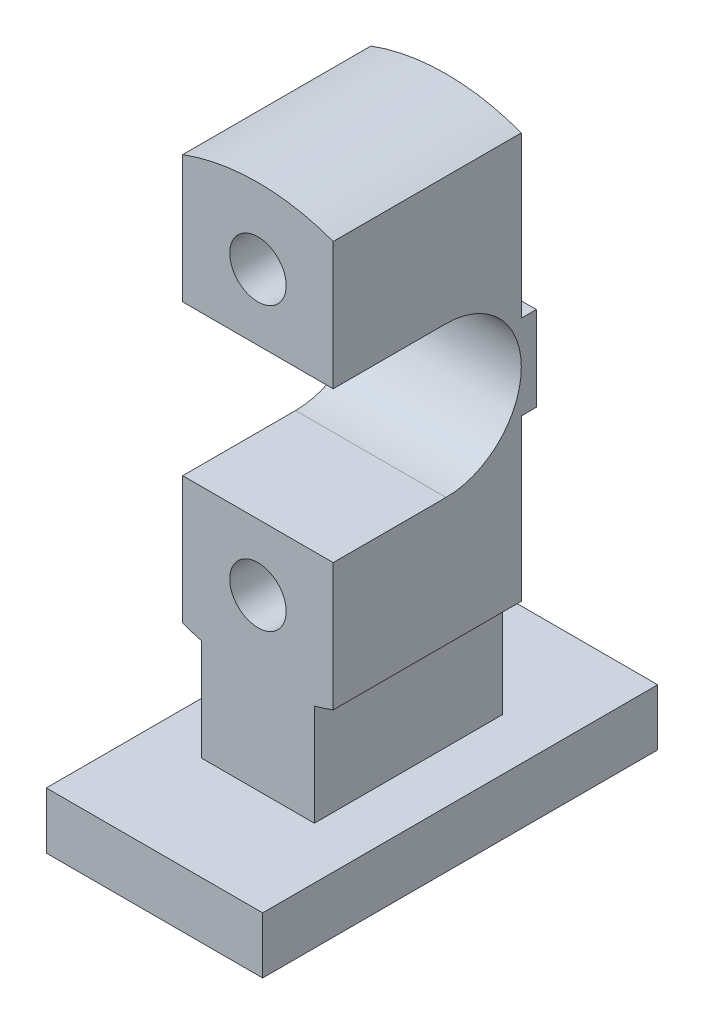
SolidWorks part; units mm, degrees
ref_plane "Front Plane" through (0, 0, 0) normal (0, 0, 1) x (1, 0, 0)
ref_plane "Top Plane" through (0, 0, 0) normal (0, 1, 0) x (1, 0, 0)
ref_plane "Right Plane" through (0, 0, 0) normal (1, 0, 0) x (0, 0, -1)
sketch "Sketch1" plane through (0, 0, 0) normal (0, 1, 0) x (1, 0, 0)
  line L1 (-57.5, -105) -> (57.5, -105)
  line L2 (-57.5, -105) -> (-57.5, 105)
  line L3 (-57.5, 105) -> (57.5, 105)
  line L4 (57.5, -105) -> (57.5, 105)
  line L5 (-57.5, -105) -> (57.5, 105) construction
  line L6 (-57.5, 105) -> (57.5, -105) construction
  point P0 (0, 0)
  dimension "D1" = 210
  dimension "D2" = 115
extrude "Boss-Extrude1" add sketch "Sketch1" along normal blind 30
sketch "Sketch2" plane through (0, 0, 0) normal (0, 0, 1) x (1, 0, 0)
  line L0 (-57.5, 30) -> (57.5, 30) construction
  line L1 (-30, 30) -> (30, 30)
  line L2 (-30, 30) -> (-30, 90)
  line L3 (-30, 90) -> (30, 90)
  line L4 (30, 30) -> (30, 90)
  dimension "D1" = 60
  dimension "D2" = 60
  dimension "D3" = 30
extrude "Boss-Extrude3" add sketch "Sketch2" along normal mid plane 100 contours L2 L1 L4 L3
sketch "Sketch3" plane through (0, 0, 0) normal (0, 0, 1) x (1, 0, 0)
  line L0 (0, 90) -> (0, 195) construction
  line L1 (-30, 90) -> (30, 90) construction
  line L2 (-40, 87.1807) -> (-40, 302.8193)
  line L3 (40, 87.1807) -> (40, 302.8193)
  arc A0 (40, 302.8193) -> (-40, 302.8193) centre (0, 195) ccw
  arc A1 (-40, 87.1807) -> (40, 87.1807) centre (0, 195) ccw
  circle A2 centre (0, 270) radius 15
  circle A3 centre (0, 120) radius 15
  point P6 (0, 142.5)
  dimension "D2" = 230
  dimension "D4" = 30
  dimension "D5" = 30
  dimension "D1" = 105
  dimension "D3" = 40
  dimension "D6" = 75
  dimension "D7" = 75
extrude "Boss-Extrude4" add sketch "Sketch3" along normal mid plane 100
sketch "Sketch7" plane through (-40, 0, 0) normal (-1, 0, 0) x (0, 0, 1)
  line L0 (101.2918, 195) -> (-133.7571, 195) construction
  line L1 (-10, 337.9486) -> (-10, 60.5649) construction
  line L2 (-50, 87.1807) -> (-50, 302.8193) construction
  line L3 (-10, 235) -> (50, 235)
  line L4 (50, 87.1807) -> (50, 302.8193) construction
  line L5 (-10, 155) -> (50, 155)
  line L6 (50, 235) -> (50, 155)
  arc A0 (-10, 235) -> (-10, 155) centre (-10, 195) ccw
  point P7 (0, 0)
  dimension "D2" = 80
  dimension "D1" = 40
  dimension "D3" = 195
sketch "Sketch8" plane through (40, 0, 0) normal (1, 0, 0) x (0, 0, -1)
  line L5 (50, 87.1807) -> (50, 302.8193) construction
  line L6 (50, 217.5) -> (58, 217.5)
  line L7 (50, 217.5) -> (50, 172.5)
  line L8 (50, 172.5) -> (58, 172.5)
  line L9 (58, 217.5) -> (58, 172.5)
  dimension "D1" = 45
  dimension "D2" = 22.5
  dimension "D3" = 8
extrude "Boss-Extrude7" add sketch "Sketch8" against normal blind 80 contours L7 L6 L9 L8
extrude "Cut-Extrude1" cut sketch "Sketch7" against normal blind 180 contours A0 L5 L6 L3
